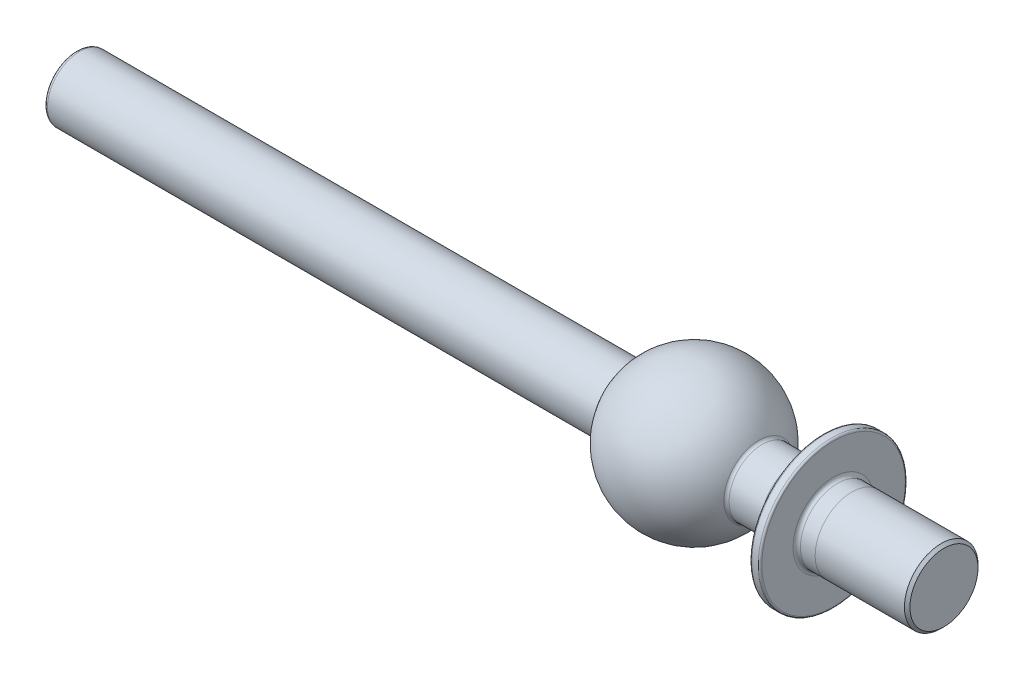
SolidWorks part; units mm, degrees
ref_plane "Front Plane" through (0, 0, 0) normal (0, 0, 1) x (1, 0, 0)
ref_plane "Top Plane" through (0, 0, 0) normal (0, 1, 0) x (1, 0, 0)
ref_plane "Right Plane" through (0, 0, 0) normal (1, 0, 0) x (0, 0, -1)
sketch "Sketch1" plane through (0, 0, 0) normal (0, 0, 1) x (1, 0, 0)
  line L0 (0, 0) -> (0, 1)
  line L1 (0, 1) -> (-3, 1)
  line L2 (-3, 1) -> (-3, 2)
  line L3 (-3, 2) -> (-3.25, 2)
  line L4 (-3.25, 2) -> (-4, 0.9)
  line L5 (-4, 0.9) -> (-5, 0.9)
  line L6 (0, 0) -> (-5, 0)
  line L7 (-5, 0) -> (-8.5845, 0)
  line L8 (-8.5845, 0) -> (-8.5845, 0.875)
  line L9 (-5, 0.9) -> (-5, 0) construction
  line L10 (-8.5845, 0) -> (-8.5845, -0.875) construction
  arc A0 (-8.5845, 0.875) -> (-5, 0.9) centre (-6.7861, 0) cw
  circle A1 centre (-6.7861, 0) radius 2 construction
  dimension "D8" = 4
  dimension "D9" = 2
  dimension "D1" = 1
  dimension "D2" = 3
  dimension "D3" = 1
  dimension "D4" = 0.25
  dimension "D5" = 1
  dimension "D6" = 1
  dimension "D7" = 0.9
  dimension "D10" = 1.75
revolve "Revolve1" add sketch "Sketch1" angle 360 about L6
chamfer "Chamfer1" distance 0.075 angle 45 1 edges at (0, 0, -1)
fillet "Fillet1" radius 0.1 3 edges at (-5, 0, -0.9) (-4, 0, -0.9) (-3, 0, -1)
fillet "Fillet2" radius 0.05 2 edges at (-3, 0, -2) (-3.25, 0, -2)
sketch "Sketch2" plane through (0, 0, 0) normal (0, 0, 1) x (1, 0, 0)
  line L0 (-2.5, 2.6966) -> (-2.5, -2.6319)
  dimension "D1" = 2.5
split line "Split Line1"
sketch "Sketch3" plane through (-8.5845, 0, 0) normal (-1, 0, 0) x (0, 0, 1)
  circle A2 centre (0, 0) radius 0.875 construction
  circle A3 centre (0, 0) radius 0.875
extrude "Boss-Extrude1" add sketch "Sketch3" along normal blind 15
fillet "Fillet3" radius 0.1 1 edges at (-23.5845, 0, 0.875)
